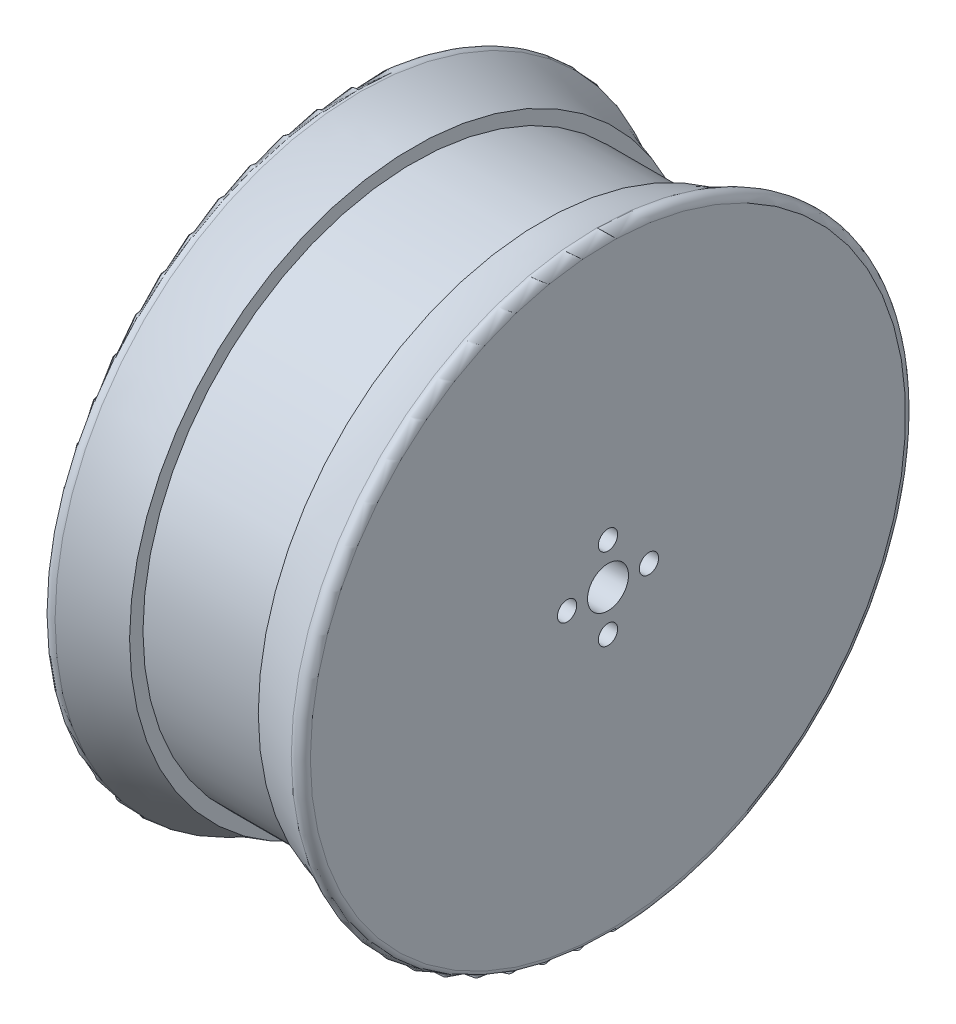
SolidWorks part; units mm, degrees
ref_plane "Front Plane" through (0, 0, 0) normal (0, 0, 1) x (1, 0, 0)
ref_plane "Top Plane" through (0, 0, 0) normal (0, 1, 0) x (1, 0, 0)
ref_plane "Right Plane" through (0, 0, 0) normal (1, 0, 0) x (0, 0, -1)
sketch "Wheel Arc" plane through (0, 0, 0) normal (0, 0, 1) x (1, 0, 0)
  line L0 (0, 0) -> (0, -103.7082) construction
  line L1 (-25.4, 0) -> (25.4, 0)
  line L2 (-40.9053, 0) -> (38.2322, 0) construction
  line L3 (-25.4, 0) -> (-25.4, -58.171)
  line L4 (25.4, 0) -> (25.4, -58.171)
  line L5 (0, -53.9082) -> (0, -52.9082) construction
  line L6 (-12.573, -52.9082) -> (12.573, -52.9082)
  line L7 (-12.573, -52.9082) -> (-12.573, -55.5215)
  line L8 (12.573, -52.9082) -> (12.573, -55.5215)
  arc A0 (23.0769, -59.5777) -> (12.573, -55.5215) centre (0, -103.7082) ccw
  arc A1 (-12.573, -55.5215) -> (-23.0769, -59.5777) centre (0, -103.7082) ccw
  arc A2 (25.4, -58.171) -> (23.0769, -59.5777) centre (23.8125, -58.171) cw
  arc A3 (-23.0769, -59.5777) -> (-25.4, -58.171) centre (-23.8125, -58.171) cw
  point P7 (0, 0)
  point P9 (0, 0)
  point P16 (0, -52.9082)
  dimension "D3" = 49.8
  dimension "D2" = 50.8
  dimension "D4" = 1
  dimension "D6" = 1.5875
  dimension "D1" = 103.7082
  dimension "D5" = 25.146
ref_axis "Wheel Axis" through (-40.9053, 0, 0) along (1, 0, 0)
revolve "Wheel" add sketch "Wheel Arc" angle 360 about axis through (-40.9053, 0, 0) along (1, 0, 0)
sketch "Flower" plane through (25.4, 0, 0) normal (1, 0, 0) x (0, 0, -1)
  line L0 (0, 0) -> (0, 8) construction
  circle A0 centre (0, 0) radius 4
  circle A1 centre (0, 8) radius 1.885
  circle A2 centre (8, 0) radius 1.885
  circle A3 centre (0, -8) radius 1.885
  circle A4 centre (-8, 0) radius 1.885
  point P14 (0, 0)
  dimension "D1" = 4
extrude "Mounting" cut sketch "Flower" against normal through all
